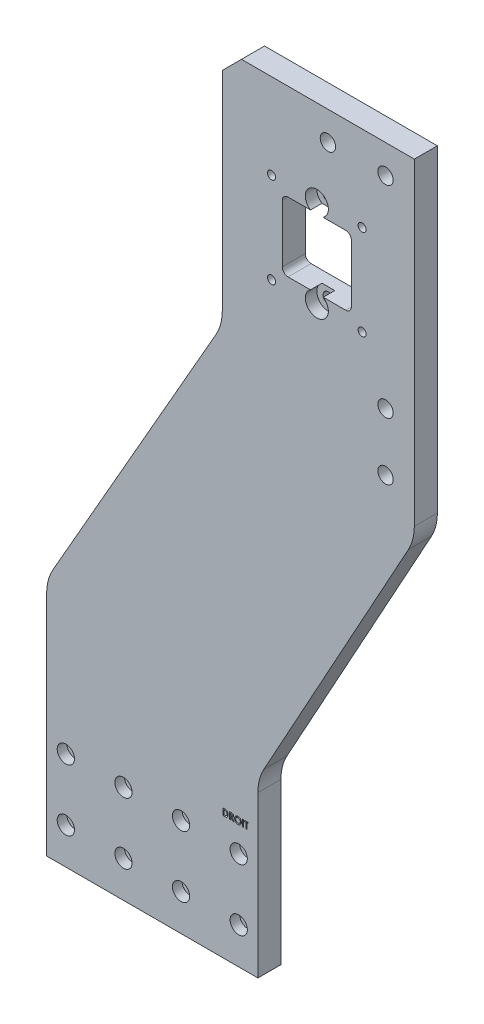
SolidWorks part; units mm, degrees
ref_plane "Plan de face" through (0, 0, 0) normal (0, 0, 1) x (1, 0, 0)
ref_plane "Plan de dessus" through (0, 0, 0) normal (0, 1, 0) x (1, 0, 0)
ref_plane "Plan de droite" through (0, 0, 0) normal (1, 0, 0) x (0, 0, -1)
sketch "Esquisse1" plane through (0, 0, 0) normal (0, 0, 1) x (1, 0, 0)
  line L0 (0, 0) -> (110, 0)
  line L1 (91.4634, 400) -> (91.4634, 291.6413)
  line L2 (101.4634, 410) -> (191.4634, 410)
  line L3 (191.4634, 410) -> (191.4634, 205) construction
  line L4 (0, 0) -> (0, 205) construction
  line L5 (0, 205) -> (191.4634, 205) construction
  line L6 (191.4634, 410) -> (191.4634, 244.4258)
  line L7 (113.0986, 95.6294) -> (188.3648, 232.3706)
  line L8 (88.1675, 279.2343) -> (3.296, 130.7657)
  line L9 (110, 0) -> (110, 83.5742)
  line L10 (0, 118.3587) -> (0, 0)
  line L11 (122.6934, 342) -> (173.0559, 342) construction
  line L12 (155.6934, 360) -> (125.6934, 360)
  line L13 (158.6934, 357) -> (158.6934, 327)
  line L14 (155.6934, 324) -> (125.6934, 324)
  line L15 (122.6934, 357) -> (122.6934, 327)
  line L16 (140.6934, 342) -> (158.6934, 324) construction
  line L17 (140.6934, 324) -> (140.6934, 360) construction
  line L18 (140.6934, 324) -> (140.6934, 314.8947) construction
  line L19 (-30.2925, 35) -> (115.1659, 35) construction
  line L20 (55, 0) -> (55, 66.4475) construction
  line L21 (10, 51) -> (40, 51) construction
  line L22 (40, 51) -> (40, 19) construction
  line L23 (40, 19) -> (10, 19) construction
  line L24 (10, 19) -> (10, 51) construction
  line L25 (101.4634, 410) -> (91.4634, 400)
  arc A0 (191.4634, 244.4258) -> (188.3648, 232.3706) centre (166.4634, 244.4258) cw
  arc A1 (91.4634, 291.6413) -> (88.1675, 279.2343) centre (66.4634, 291.6413) cw
  arc A2 (3.296, 130.7657) -> (0, 118.3587) centre (25, 118.3587) ccw
  arc A3 (113.0986, 95.6294) -> (110, 83.5742) centre (135, 83.5742) ccw
  arc A4 (122.6934, 327) -> (125.6934, 324) centre (125.6934, 327) ccw
  arc A5 (158.6934, 327) -> (155.6934, 324) centre (155.6934, 327) cw
  arc A6 (125.6934, 360) -> (122.6934, 357) centre (125.6934, 357) ccw
  arc A7 (158.6934, 357) -> (155.6934, 360) centre (155.6934, 357) ccw
  circle A10 centre (40, 51) radius 2.5
  circle A11 centre (40, 19) radius 2.5
  circle A12 centre (164.2634, 318.43) radius 2.1
  circle A13 centre (117.1234, 318.43) radius 2.1
  circle A14 centre (164.2634, 365.57) radius 2.1
  circle A15 centre (117.1234, 365.57) radius 2.1
  circle A16 centre (10, 51) radius 2.5
  circle A17 centre (10, 19) radius 2.5
  circle A18 centre (100, 51) radius 2.5
  circle A19 centre (100, 19) radius 2.5
  circle A20 centre (70, 19) radius 2.5
  circle A21 centre (70, 51) radius 2.5
  circle A22 centre (176.4634, 395) radius 4
  circle A23 centre (146.4634, 395) radius 4
  circle A24 centre (176.4634, 290) radius 4
  circle A25 centre (176.4634, 260) radius 4
  circle A26 centre (140.6934, 319) radius 2.75
  circle A27 centre (140.6934, 365) radius 2.75
  point P3 (91.4634, 410)
  point P17 (191.4634, 238)
  point P20 (91.4634, 285)
  point P23 (0, 125)
  point P26 (110, 90)
  point P29 (122.6934, 324)
  point P34 (122.6934, 360)
  point P37 (158.6934, 360)
  dimension "D14" = 25
  dimension "D15" = 25
  dimension "D16" = 25
  dimension "D17" = 25
  dimension "D18" = 3
  dimension "D24" = 47.14
  dimension "D26" = 30
  dimension "D30" = 8
  dimension "D35" = 8
  dimension "D37" = 8
  dimension "D39" = 5.5
  dimension "D40" = 23
  dimension "D1" = 125
  dimension "D2" = 205
  dimension "D3" = 205
  dimension "D4" = 110
  dimension "D5" = 100
  dimension "D6" = 125
  dimension "D7" = 172
  dimension "D8" = 90
  dimension "D9" = 110.1414
  dimension "D10" = 36
  dimension "D11" = 36
  dimension "D12" = 50
  dimension "D13" = 32.77
  dimension "D22" = 115.2874
  dimension "D23" = 110.6152
  dimension "D25" = 47.14
  dimension "D20" = 35
  dimension "D27" = 15
  dimension "D28" = 32
  dimension "D29" = 16
  dimension "D31" = 15
  dimension "D32" = 15
  dimension "D34" = 105
  dimension "D38" = 30
  dimension "D33" = 2
extrude "Boss.-Extru.1" add sketch "Esquisse1" along normal blind 12
sketch "Esquisse2" plane through (0, 0, 12) normal (0, 0, 1) x (1, 0, 0)
  circle A0 centre (10, 19) radius 4.5
  circle A1 centre (40, 19) radius 4.5
  circle A2 centre (70, 19) radius 4.5
  circle A3 centre (100, 19) radius 4.5
  circle A4 centre (40, 51) radius 4.5
  circle A5 centre (70, 51) radius 4.5
  circle A6 centre (100, 51) radius 4.5
  circle A7 centre (10, 51) radius 4.5
  dimension "D1" = 4
  dimension "D2" = 2
extrude "Enlèv. mat.-Extru.1" cut sketch "Esquisse2" against normal blind 5
sketch "Esquisse3" plane through (0, 0, 12) normal (0, 0, 1) x (1, 0, 0)
  text T0 "<b>DROIT</b>"
extrude "Enlèv. mat.-Extru.2" cut sketch "Esquisse3" against normal blind 1
sketch "Esquisse6" plane through (0, 0, 0) normal (0, -1, 0) x (1, 0, 0)
  line L0 (0, 6) -> (110, 6) construction
  line L1 (0, 12) -> (0, 0) construction
  line L2 (110, 12) -> (110, 0) construction
  line L3 (110, 12) -> (110, 0) construction
  circle A1 centre (15, 6) radius 2.5
  circle A2 centre (55, 6) radius 2.5
  circle A3 centre (95, 6) radius 2.5
  dimension "D1" = 5
  dimension "D2" = 5
  dimension "D3" = 5
  dimension "D4" = 15
  dimension "D5" = 55
  dimension "D6" = 15
extrude "Enlèv. mat.-Extru.5" cut sketch "Esquisse6" against normal blind 10
sketch "Esquisse8" plane through (0, 0, 12) normal (0, 0, 1) x (1, 0, 0)
  circle A0 centre (140.6934, 365) radius 6
  circle A1 centre (140.6934, 319) radius 6
  dimension "D1" = 12
  dimension "D2" = 12
extrude "Enlèv. mat.-Extru.6" cut sketch "Esquisse8" against normal blind 6
